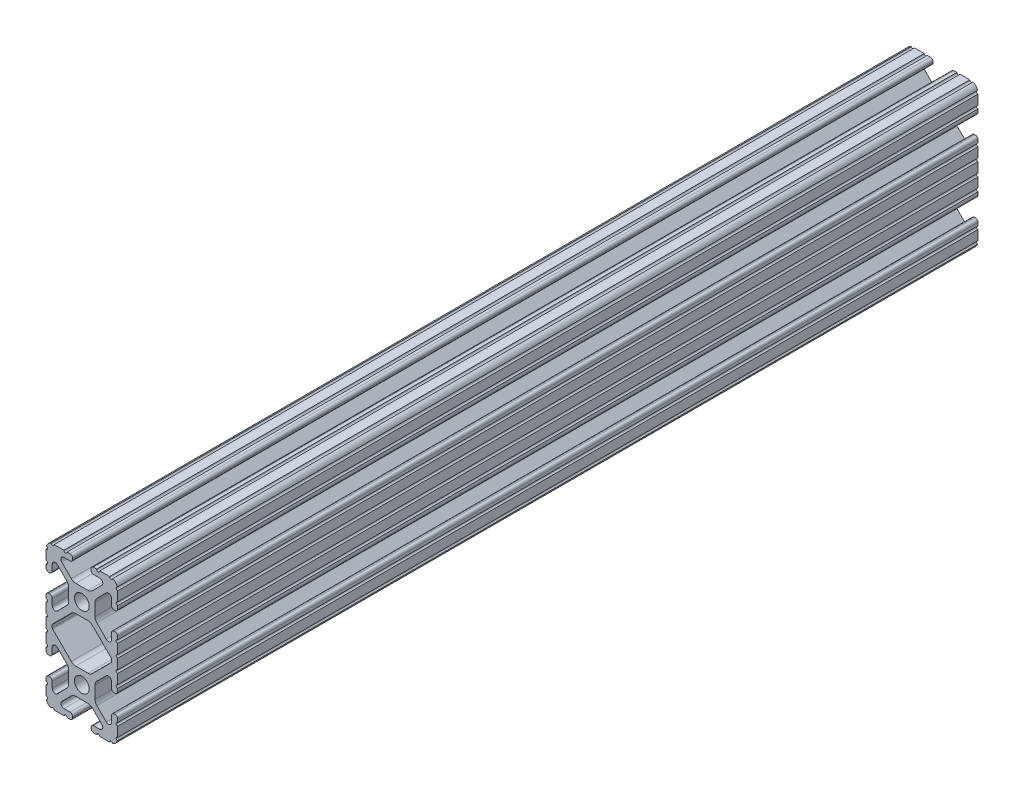
SolidWorks part; units mm, degrees
material "6061 Alloy"
ref_plane "Front Plane" through (0, 0, 0) normal (0, 0, 1) x (1, 0, 0)
ref_plane "Top Plane" through (0, 0, 0) normal (0, 1, 0) x (1, 0, 0)
ref_plane "Right Plane" through (0, 0, 0) normal (1, 0, 0) x (0, 0, -1)
sketch "Sketch2" plane through (0, 0, 0) normal (0, 0, 1) x (1, 0, 0)
  line L0 (0, 25.4) -> (0, -25.4) construction
  line L1 (-12.7, 0) -> (12.7, 0) construction
  line L2 (3.2512, -25.4) -> (12.7, -25.4)
  line L3 (12.7, -25.4) -> (12.7, -15.9512)
  line L4 (3.2512, -25.4) -> (3.2512, -23.1902)
  line L5 (3.2512, -23.1902) -> (8.9276, -23.1902)
  line L6 (8.9276, -23.1902) -> (3.0856, -17.3482)
  line L7 (0, -12.7) -> (12.7, -25.4) construction
  line L8 (12.7, -15.9512) -> (10.4902, -15.9512)
  line L9 (10.4902, -15.9512) -> (10.4902, -21.6276)
  line L10 (10.4902, -21.6276) -> (4.6482, -15.7856)
  line L11 (3.2512, -25.4) -> (0, -25.4) construction
  line L12 (0, -25.4) -> (-3.2512, -25.4) construction
  line L13 (-3.2512, -25.4) -> (-12.7, -25.4) construction
  line L14 (12.7, 25.4) -> (-12.7, 25.4) construction
  line L15 (0, 12.7) -> (0, -12.7) construction
  circle A0 centre (0, -12.7) radius 2.6035
  arc A1 (6.3485, -23.1902) -> (7.1039, -21.3665) centre (6.3485, -22.1219) ccw construction
  point P8 (0, -17.3482)
  point P16 (-2.6035, -12.7)
  point P18 (2.6035, -12.7)
  point P19 (0, -10.0965)
  point P20 (0, -15.3035)
  point P27 (-12.7, -25.4)
  point P30 (0, 25.4)
  point P31 (12.7, 25.4)
  point P32 (-12.7, 25.4)
  point P33 (12.7, -25.4)
  point P34 (0, -12.7)
  point P35 (0, 12.7)
  point P37 (0, 0)
  point P38 (-3.2512, -25.4)
  point P39 (3.2512, -25.4)
  dimension "Center Hole Diameter" = 5.207
  dimension "Rail Height" = 50.8
  dimension "Rail Width" = 25.4
  dimension "T-Slot Width" = 6.5024
  dimension "Slot Inner Width" = 14.8336
  dimension "Thickness" = 2.2098
  dimension "Slot Depth" = 5.842
  dimension "D1" = 2.2098
  dimension "C to C" = 25.4
sketch "Sketch3" plane through (0, 0, 0) normal (1, 0, 0) x (0, 0, -1)
  line L0 (-152.4, -25.4) -> (152.4, -25.4) construction
  line L1 (-101.6, 0) -> (101.6, 0) construction
  point P6 (-152.4, -25.4)
  point P8 (-101.6, 0)
  point P9 (101.6, 0)
  point P10 (152.4, -25.4)
  dimension "Length" = 304.8
  dimension "D1" = 50.8
sketch "Sketch4" plane through (0, 0, 0) normal (0, 0, 1) x (1, 0, 0)
  line L0 (4.1904, -25.4) -> (10.1173, -25.4)
  line L1 (3.2512, -25.4) -> (12.7, -25.4) construction
  line L2 (3.2512, -25.4) -> (3.2512, -23.1902) construction
  line L3 (3.2512, -23.1902) -> (8.9276, -23.1902) construction
  line L4 (3.2512, -24.1294) -> (3.2512, -24.4608)
  line L5 (4.1904, -23.1902) -> (6.3485, -23.1902)
  line L6 (0, -17.3482) -> (2.164, -17.3482)
  line L7 (8.9276, -23.1902) -> (3.0856, -17.3482) construction
  line L8 (3.7373, -17.9999) -> (7.1039, -21.3665)
  line L9 (12.7, -25.4) -> (12.7, -15.9512) construction
  line L10 (10.4902, -21.6276) -> (4.6482, -15.7856) construction
  line L11 (10.4902, -15.9512) -> (10.4902, -21.6276) construction
  line L12 (10.4902, -19.0485) -> (10.4902, -16.8904)
  line L13 (12.7, -15.9512) -> (10.4902, -15.9512) construction
  line L14 (11.4294, -15.9512) -> (11.7608, -15.9512)
  line L15 (12.7, -16.8904) -> (12.7, -22.8173)
  line L16 (8.6665, -19.8039) -> (5.2999, -16.4373)
  line L17 (4.6482, -12.7) -> (4.6482, -14.864)
  line L19 (0, -17.3482) -> (0, -15.3035)
  line L20 (0, 25.4) -> (0, -25.4) construction
  line L21 (4.6482, -12.7) -> (2.6035, -12.7)
  arc A0 (3.2512, -24.4608) -> (4.1904, -25.4) centre (4.1904, -24.4608) ccw
  circle A1 centre (0, -12.7) radius 2.6035 construction
  arc A2 (3.2512, -24.1294) -> (4.1904, -23.1902) centre (4.1904, -24.1294) cw
  arc A3 (6.3485, -23.1902) -> (7.1039, -21.3665) centre (6.3485, -22.1219) ccw
  arc A4 (2.164, -17.3482) -> (3.7373, -17.9999) centre (2.164, -19.5732) cw
  arc A5 (10.1173, -25.4) -> (12.7, -22.8173) centre (10.1173, -22.8173) ccw
  arc A6 (8.6665, -19.8039) -> (10.4902, -19.0485) centre (9.4219, -19.0485) ccw
  arc A7 (10.4902, -16.8904) -> (11.4294, -15.9512) centre (11.4294, -16.8904) cw
  arc A8 (11.7608, -15.9512) -> (12.7, -16.8904) centre (11.7608, -16.8904) cw
  arc A9 (5.2999, -16.4373) -> (4.6482, -14.864) centre (6.8732, -14.864) cw
  arc A11 (0, -15.3035) -> (2.6035, -12.7) centre (0, -12.7) ccw
  dimension "D1" = 2.5827
  dimension "D2" = 2.225
  dimension "D3" = 0.9392
extrude "Boss-Extrude1" add sketch "Sketch4" along normal mid plane 304.8
sketch "Sketch5" plane through (0, 0, 0) normal (0, 0, 1) x (1, 0, 0)
  line L0 (3.2512, -25.4) -> (12.7, -25.4) construction
  line L1 (4.1904, -23.1902) -> (6.3485, -23.1902) construction
  line L3 (0, -12.7) -> (12.7, -25.4) construction
  line L4 (6.3485, -23.1902) -> (6.3485, -25.4) construction
  line L5 (8.9276, -23.1902) -> (3.0856, -17.3482) construction
  circle A0 centre (10.3562, -25.4) radius 0.5524
  circle A1 centre (5.796, -25.4) radius 0.5524
  circle A2 centre (12.7, -23.0562) radius 0.5524
  circle A3 centre (12.7, -18.496) radius 0.5524
  point P10 (5.2694, -23.1902)
  point P12 (9.4219, -19.0485)
  dimension "D1" = 1.1049
extrude "Cut-Extrude1" cut sketch "Sketch5" against normal through all both and the other way through all
mirror "Mirror1" about plane through (4.6482, -12.7, 152.4) normal (0, -1, 0) of bodies 137 134
sketch "Sketch6" plane through (0, 0, 0) normal (0, 0, 1) x (1, 0, 0)
  line L0 (12.7, -1.7914) -> (12.7, 0)
  line L1 (12.7, 0) -> (9.8037, 0)
  line L2 (-12.7, 0) -> (12.7, 0) construction
  line L3 (9.8037, 0) -> (9.8037, -2.3438)
  line L4 (9.8037, -2.3438) -> (12.1476, -2.3438)
  circle A0 centre (12.7, -2.3438) radius 0.5524 construction
  arc A1 (12.7, -1.7914) -> (12.1476, -2.3438) centre (12.7, -2.3438) ccw
  arc A4 (12.58, -1.8046) -> (12.7, -2.8963) centre (12.7, -2.3438) ccw construction
  arc A6 (9.8037, 0) -> (10.8954, -0.12) centre (10.3562, 0) ccw construction
extrude "Boss-Extrude2" add sketch "Sketch6" along normal mid plane 304.8
sketch "Sketch7" plane through (0, 0, 0) normal (0, 0, 1) x (1, 0, 0)
  line L0 (5.4206, -5.7168) -> (10.3284, -0.809)
  line L1 (3.7373, -7.4001) -> (7.1039, -4.0335) construction
  line L2 (10.4902, -0.4184) -> (10.4902, 0)
  line L3 (0, 0) -> (10.4902, 0)
  line L4 (-12.7, 0) -> (12.7, 0) construction
  line L5 (0, 0) -> (5.4206, -5.7168)
  arc A0 (10.3284, -0.809) -> (10.4902, -0.4184) centre (9.9377, -0.4184) ccw
  arc A3 (12.7, -1.7914) -> (12.7, -2.8963) centre (12.7, -2.3438) ccw construction
extrude "Cut-Extrude2" cut sketch "Sketch7" against normal through all both and the other way through all
mirror "Mirror2" about plane through (0, 0, 0) normal (0, 1, 0) of bodies 139 135
mirror "Mirror3" about plane through (0, 0, 0) normal (1, 0, 0) of bodies 136
equation "\"D1@Boss-Extrude1\"=\"Length@Sketch3\""
equation "\"D1@Sketch2\"=\"Thickness@Sketch2\""
equation "\"D2@Sketch4\"=\"Slot Inner Width@Sketch2\"*0.15"
equation "\"D1@Sketch4\"=\"D3@Sketch4\"*2.75"
equation "\"D3@Sketch4\"=\"Thickness@Sketch2\"*0.425"
equation "\"D1@Sketch5\"=\"Thickness@Sketch2\"*0.5"
equation "\"D1@Boss-Extrude2\"=\"Length@Sketch3\""
